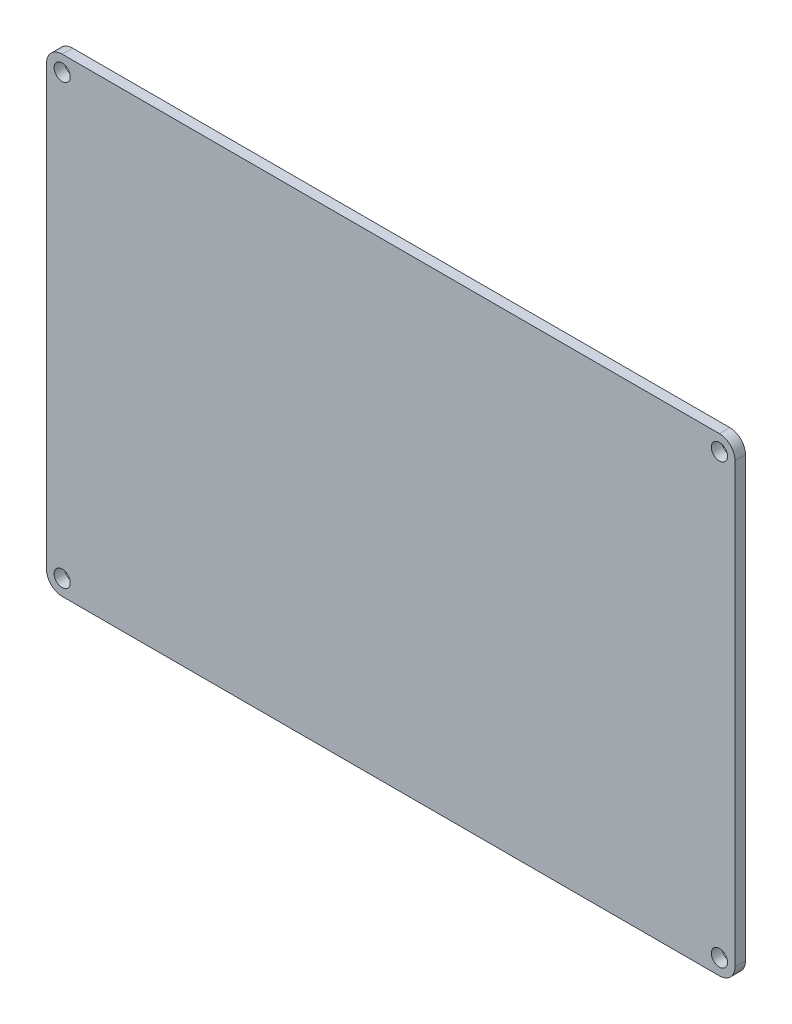
SolidWorks part; units mm, degrees
ref_plane "Front Plane" through (0, 0, 0) normal (0, 0, 1) x (1, 0, 0)
ref_plane "Top Plane" through (0, 0, 0) normal (0, 1, 0) x (1, 0, 0)
ref_plane "Right Plane" through (0, 0, 0) normal (1, 0, 0) x (0, 0, -1)
sketch "Sketch1" plane through (0, 0, 0) normal (0, 0, 1) x (1, 0, 0)
  line L1 (-62.9793, -45) -> (62.9793, -45)
  line L2 (-65.9793, -42) -> (-65.9793, 42)
  line L3 (-62.9793, 45) -> (62.9793, 45)
  line L4 (65.9793, -42) -> (65.9793, 42)
  line L5 (-65.9793, -45) -> (65.9793, 45) construction
  line L6 (-65.9793, 45) -> (65.9793, -45) construction
  arc A6 (62.9793, 45) -> (65.9793, 42) centre (62.9793, 42) cw
  arc A7 (62.9793, -45) -> (65.9793, -42) centre (62.9793, -42) ccw
  arc A8 (-62.9793, -45) -> (-65.9793, -42) centre (-62.9793, -42) cw
  arc A9 (-65.9793, 42) -> (-62.9793, 45) centre (-62.9793, 42) cw
  circle A10 centre (-62.9793, 42) radius 1.55
  circle A11 centre (-62.9793, -42) radius 1.55
  circle A12 centre (62.9793, -42) radius 1.55
  circle A13 centre (62.9793, 42) radius 1.55
  point P0 (0, 0)
  point P8 (35.4793, 0)
  dimension "D17" = 3
  dimension "D2" = 3.1
  dimension "D3" = 3.1
  dimension "D4" = 3.1
  dimension "D5" = 3.1
  dimension "D6" = 0
  dimension "D7" = 90
  dimension "D16" = 131.9586
extrude "Boss-Extrude1" add sketch "Sketch1" along normal blind 2
